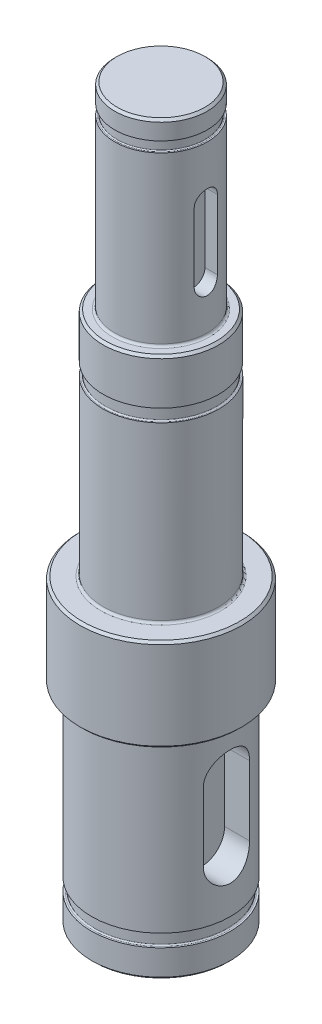
SolidWorks part; units mm, degrees
ref_plane "Front" through (0, 0, 0) normal (0, 0, 1) x (1, 0, 0)
ref_plane "Top" through (0, 0, 0) normal (0, 1, 0) x (1, 0, 0)
ref_plane "Right" through (0, 0, 0) normal (1, 0, 0) x (0, 0, -1)
sketch "Sketch1" plane through (0, 0, 0) normal (1, 0, 0) x (0, 0, -1)
  line L0 (0, 27.8978) -> (0, -35.2793) construction
  line L1 (0, 0) -> (0, -63)
  line L2 (0, -63) -> (6, -63)
  line L3 (6, -63) -> (6, -45)
  line L4 (6, -45) -> (7, -45)
  line L5 (7, -45) -> (7, -37)
  line L6 (7, -37) -> (5, -37)
  line L8 (4, 0) -> (0, 0)
  line L9 (5, -37) -> (5, -17)
  line L10 (5, -17) -> (4, -17)
  line L11 (4, -17) -> (4, 0)
  dimension "D1" = 6
  dimension "D2" = 1
  dimension "D3" = 2
  dimension "D4" = 8
  dimension "D5" = 18
  dimension "D6" = 20
  dimension "D7" = 1
  dimension "D8" = 17
revolve "Revolve1" add sketch "Sketch1" angle 360 about L0
ref_plane "Plane1" through (0, 27.8978, 0) normal (-1, 0, 0) x (0, 0, 1)
sketch "Sketch3" plane through (0, 27.8978, 0) normal (-1, 0, 0) x (0, 0, 1)
  line L0 (5.86, -88.4978) -> (7.2, -88.4978)
  line L1 (7.2, -88.4978) -> (7.2, -87.3978)
  line L2 (7.2, -87.3978) -> (5.86, -87.3978)
  line L3 (5.75, -87.5078) -> (5.75, -88.3878)
  line L4 (0, -50) -> (0, 50) construction
  line L5 (-7, -72.8978) -> (7, -72.8978) construction
  arc A0 (5.75, -88.3878) -> (5.86, -88.4978) centre (5.86, -88.3878) ccw
  arc A1 (5.75, -87.5078) -> (5.86, -87.3978) centre (5.86, -87.5078) cw
  dimension "D1" = 0.11
  dimension "D2" = 0.11
  dimension "D3" = 14.5
  dimension "D4" = 5.75
  dimension "D5" = 1.1
  dimension "D6" = 1.34
revolve "Groove for BS 3673 P4 - S012M, External Circlip1" cut sketch "Sketch3"
ref_plane "Plane2" through (0, 27.8978, 0) normal (-1, 0, 0) x (0, 0, 1)
sketch "Sketch5" plane through (0, 27.8978, 0) normal (-1, 0, 0) x (0, 0, 1)
  line L0 (4.91, -49.8978) -> (6, -49.8978)
  line L1 (6, -49.8978) -> (6, -48.7978)
  line L2 (6, -48.7978) -> (4.91, -48.7978)
  line L3 (4.8, -48.9078) -> (4.8, -49.7878)
  line L4 (0, -50) -> (0, 50) construction
  line L5 (7, -64.8978) -> (-7, -64.8978) construction
  arc A0 (4.8, -49.7878) -> (4.91, -49.8978) centre (4.91, -49.7878) ccw
  arc A1 (4.8, -48.9078) -> (4.91, -48.7978) centre (4.91, -48.9078) cw
  dimension "D1" = 0.11
  dimension "D2" = 0.11
  dimension "D3" = 15
  dimension "D4" = 1.1
  dimension "D5" = 1.09
  dimension "D6" = 4.8
revolve "Groove for BS 3673 P4 - S010M, External Circlip1" cut sketch "Sketch5" angle 360 about L4
ref_plane "Plane3" through (0, 27.8978, 0) normal (-1, 0, 0) x (0, 0, 1)
sketch "Sketch7" plane through (0, 27.8978, 0) normal (-1, 0, 0) x (0, 0, 1)
  line L0 (3.89, -30.3978) -> (4.8, -30.3978)
  line L1 (4.8, -30.3978) -> (4.8, -29.4978)
  line L2 (4.8, -29.4978) -> (3.89, -29.4978)
  line L3 (3.8, -29.5878) -> (3.8, -30.3078)
  line L4 (0, -44.1028) -> (0, 55.8972) construction
  line L5 (5, -44.8978) -> (-5, -44.8978) construction
  arc A0 (3.8, -30.3078) -> (3.89, -30.3978) centre (3.89, -30.3078) ccw
  arc A1 (3.8, -29.5878) -> (3.89, -29.4978) centre (3.89, -29.5878) cw
  dimension "D1" = 0.09
  dimension "D2" = 0.09
  dimension "D3" = 0.9
  dimension "D4" = 0.91
  dimension "D5" = 3.8
  dimension "D6" = 14.5
revolve "Groove for BS 3673 P4 - S008M, External Circlip1" cut sketch "Sketch7" angle 360 about L4
chamfer "Chamfer1" distance 0.2 angle 45 1 edges at (0, -37, 7)
chamfer "Chamfer2" distance 0.2 angle 45 4 edges at (0, 0, 4) (0, -17, 5) (0, -63, 6) (0, -45, 7)
fillet "Fillet1" radius 0.2 3 edges at (0, -45, 6) (0, -37, 5) (0, -17, 4)
ref_plane "Plane4" through (3.5, 0, 0) normal (1, 0, 0) x (0, 0, -1)
sketch "Sketch8" plane through (3.5, 0, 0) normal (1, 0, 0) x (0, 0, -1)
  line L0 (0, 16.1041) -> (0, -77.4339) construction
  line L1 (0, -49) -> (0, -55) construction
  line L2 (2, -49) -> (2, -55)
  line L3 (-2, -49) -> (-2, -55)
  line L4 (-6.8, -45) -> (6.8, -45) construction
  arc A0 (2, -49) -> (-2, -49) centre (0, -49) ccw
  arc A1 (-2, -55) -> (2, -55) centre (0, -55) ccw
  point P5 (0, -52)
  dimension "D1" = 2
  dimension "D2" = 6
  dimension "D3" = 7
extrude "Cut-Extrude1" cut sketch "Sketch8" along normal through all
ref_plane "Plane5" through (2.8, 0, 0) normal (1, 0, 0) x (0, 0, -1)
sketch "Sketch9" plane through (2.8, 0, 0) normal (1, 0, 0) x (0, 0, -1)
  line L0 (0, -7) -> (0, -13) construction
  line L1 (1, -7) -> (1, -13)
  line L2 (-1, -7) -> (-1, -13)
  line L3 (4.8, -17) -> (-4.8, -17) construction
  arc A0 (1, -7) -> (-1, -7) centre (0, -7) ccw
  arc A1 (-1, -13) -> (1, -13) centre (0, -13) ccw
  point P3 (0, -10)
  dimension "D1" = 1
  dimension "D2" = 6
  dimension "D3" = 7
extrude "Cut-Extrude2" cut sketch "Sketch9" along normal through all
